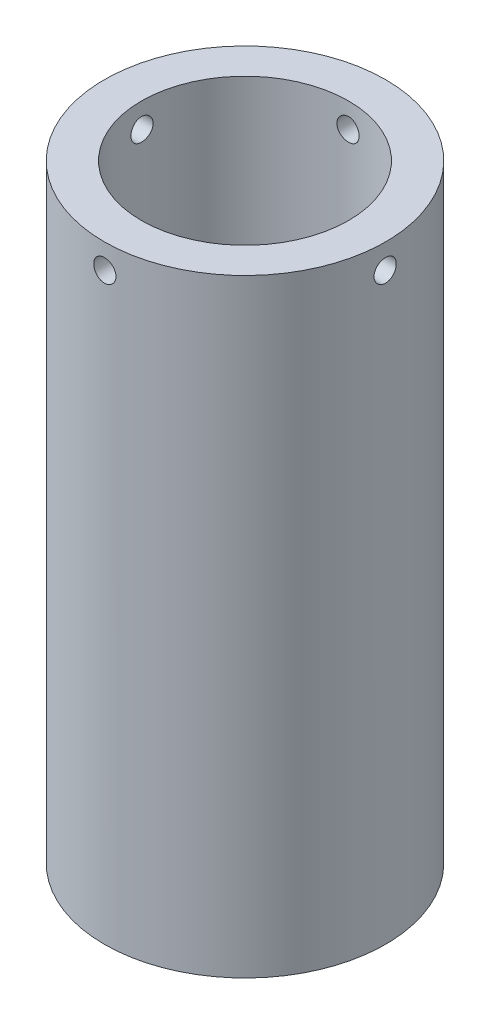
SolidWorks part; units mm, degrees
ref_plane "Front Plane" through (0, 0, 0) normal (0, 0, 1) x (1, 0, 0)
ref_plane "Top Plane" through (0, 0, 0) normal (0, 1, 0) x (1, 0, 0)
ref_plane "Right Plane" through (0, 0, 0) normal (1, 0, 0) x (0, 0, -1)
sketch "Sketch1" plane through (0, 0, 0) normal (0, 1, 0) x (1, 0, 0)
  circle A0 centre (0, 0) radius 28.5
  circle A1 centre (0, 0) radius 21
  dimension "D1" = 57
  dimension "D2" = 42
extrude "Boss-Extrude1" add sketch "Sketch1" along normal mid plane 123.35
sketch "Sketch2" plane through (0, 0, 0) normal (0, 0, 1) x (1, 0, 0)
  line L3 (21, 61.675) -> (-21, 61.675) construction
  circle A0 centre (0, 56.675) radius 2.25
  dimension "D1" = 4.5
  dimension "D2" = 5
extrude "Cut-Extrude1" cut sketch "Sketch2" against normal through all
pattern_circular "CirPattern1" count 4 every 90 about axis through (0, 61.675, 0) along (0, -1, 0) of "Cut-Extrude1"
sketch "Sketch3" plane through (0, -61.675, 0) normal (0, -1, 0) x (1, 0, 0)
  line L0 (0, 28.5) -> (0, 21) construction
  circle A0 centre (0, 0) radius 28.5 construction
  arc A1 (2.25, 20.8791) -> (-2.25, 20.8791) centre (0, 0) ccw construction
  circle A2 centre (0, 24.75) radius 2.25
  circle A3 centre (24.75, 0) radius 2.25
  circle A4 centre (0, -24.75) radius 2.25
  circle A5 centre (-24.75, 0) radius 2.25
  point P10 (-32.583, 3.3519)
  point P11 (0, 0)
  point P12 (-2.4812, -1.8434)
  point P19 (0, 0)
  dimension "D1" = 4.5
  dimension "D2" = 4
extrude "Cut-Extrude2" cut sketch "Sketch3" against normal blind 6.5
